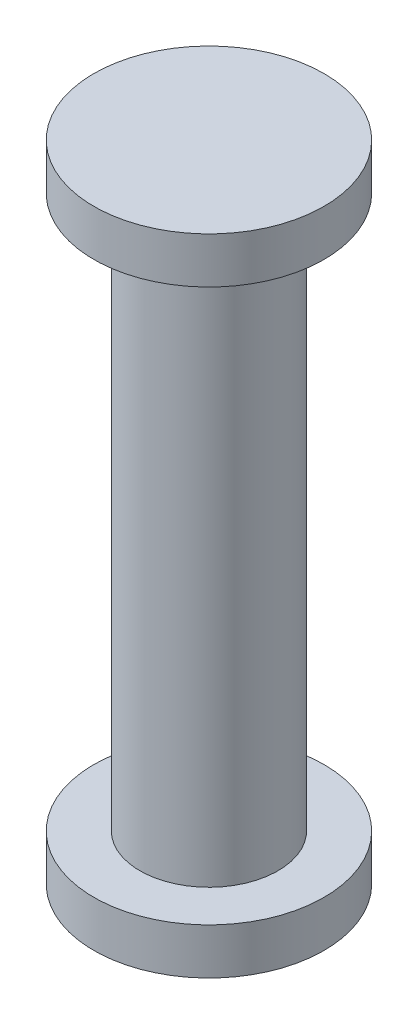
SolidWorks part; units mm, degrees
ref_plane "Front Plane" through (0, 0, 0) normal (0, 0, 1) x (1, 0, 0)
ref_plane "Top Plane" through (0, 0, 0) normal (0, 1, 0) x (1, 0, 0)
ref_plane "Right Plane" through (0, 0, 0) normal (1, 0, 0) x (0, 0, -1)
sketch "Sketch1" plane through (0, 0, 0) normal (0, 0, 1) x (1, 0, 0)
  line L0 (0, 0) -> (0, 14)
  line L1 (0, 14) -> (-2.5, 14)
  line L2 (-2.5, 14) -> (-2.5, 13)
  line L3 (-2.5, 13) -> (-1.5, 13)
  line L5 (-1.5, 1) -> (-2.5, 1)
  line L6 (-2.5, 1) -> (-2.5, 0)
  line L7 (-2.5, 0) -> (0, 0)
  line L8 (-1.5, 13) -> (-1.5, 1)
  dimension "D1" = 14
  dimension "D2" = 1
  dimension "D3" = 2.5
  dimension "D4" = 1.5
revolve "Revolve1" add sketch "Sketch1" angle 360 about L0
